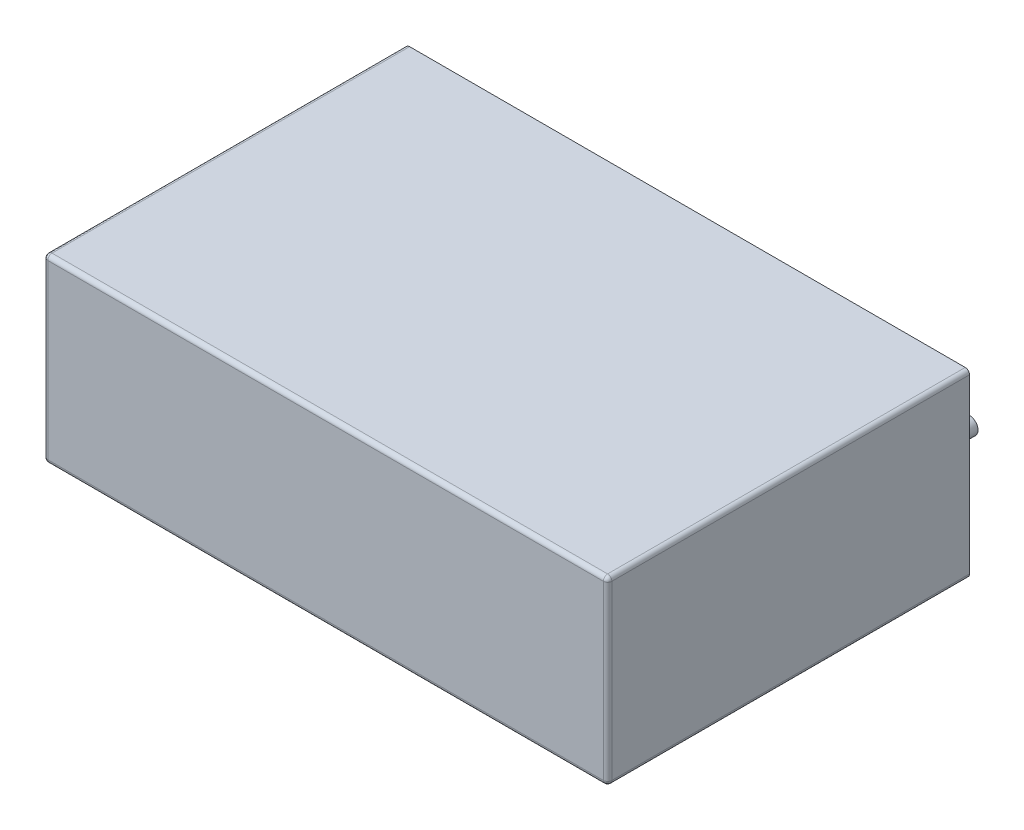
SolidWorks part; units mm, degrees
material "Duranickel(R) 301"
ref_plane "Front Plane" through (0, 0, 0) normal (0, 0, 1) x (1, 0, 0)
ref_plane "Top Plane" through (0, 0, 0) normal (0, 1, 0) x (1, 0, 0)
ref_plane "Right Plane" through (0, 0, 0) normal (1, 0, 0) x (0, 0, -1)
sketch "Sketch1" plane through (0, 0, 0) normal (0, 0, 1) x (1, 0, 0)
  line L1 (13.25, 4.25) -> (-13.25, 4.25)
  line L2 (13.25, 4.25) -> (13.25, -4.25)
  line L3 (13.25, -4.25) -> (-13.25, -4.25)
  line L4 (-13.25, 4.25) -> (-13.25, -4.25)
  line L5 (13.25, 4.25) -> (-13.25, -4.25) construction
  line L6 (13.25, -4.25) -> (-13.25, 4.25) construction
  point P0 (0, 0)
  dimension "D1" = 26.5
  dimension "D2" = 8.5
extrude "Extrude1" add sketch "Sketch1" along normal blind 17
fillet "Fillet1" radius 0.2 8 edges at (13.25, 4.25, 8.5) (13.25, -4.25, 8.5) (13.25, 0, 17) (0, 4.25, 17) (0, -4.25, 17) (-13.25, -4.25, 8.5) (-13.25, 4.25, 8.5) (-13.25, 0, 17)
sketch "Sketch3" plane through (0, -4.25, 0) normal (0, -1, 0) x (1, 0, 0)
  line L0 (-9, 10.1831) -> (9, 10.1831) construction
  text T0 "MKP X2 \r\n470nF \r\n275V AC" font "Century Gothic" height in points 6
extrude "Boss-Extrude1" add sketch "Sketch3" along normal blind 0.01
sketch "Sketch4" plane through (0, 0, 0) normal (0, 0, -1) x (-1, 0, 0)
  line L0 (-13.25, -4.05) -> (-13.25, 4.05) construction
  line L1 (-13, 4) -> (13, 4)
  line L2 (-13, 4) -> (-13, -4)
  line L3 (-13, -4) -> (13, -4)
  line L4 (13, 4) -> (13, -4)
  line L5 (-13, 4) -> (13, -4) construction
  line L6 (-13, -4) -> (13, 4) construction
  line L7 (-13.05, 4.25) -> (13.05, 4.25) construction
  point P0 (0, 0)
  dimension "D1" = 0.25
  dimension "D2" = 0.25
extrude "Cut-Extrude1" cut sketch "Sketch4" against normal blind 0.5
sketch "Sketch5" plane through (0, -4.25, 0) normal (0, -1, 0) x (1, 0, 0)
  line L0 (-13.05, 0) -> (13.05, 0) construction
  line L1 (-9.75, 0) -> (9.75, 0) construction
  line L2 (-9.75, 0) -> (-9.75, 0.4)
  line L3 (-9.75, 0.4) -> (9.75, 0.4)
  line L4 (9.75, 0) -> (9.75, 0.4)
  line L5 (-13.25, 0) -> (-13.25, 16.8) construction
  point P6 (0, 0)
  dimension "D1" = 0.4
  dimension "D2" = 3.5
extrude "Cut-Extrude5" cut sketch "Sketch5" against normal blind 6 and the other way through all
sketch "Sketch2" plane through (0, 0, 0.5) normal (0, 0, -1) x (-1, 0, 0)
  line L0 (-11.25, 0) -> (11.25, 0) construction
  circle A0 centre (-11.25, 0) radius 0.4
  circle A1 centre (11.25, 0) radius 0.4
  point P0 (0, 0)
  dimension "D1" = 0.8
  dimension "D2" = 22.5
extrude "Extrude2" add sketch "Sketch2" along normal blind 2.5
